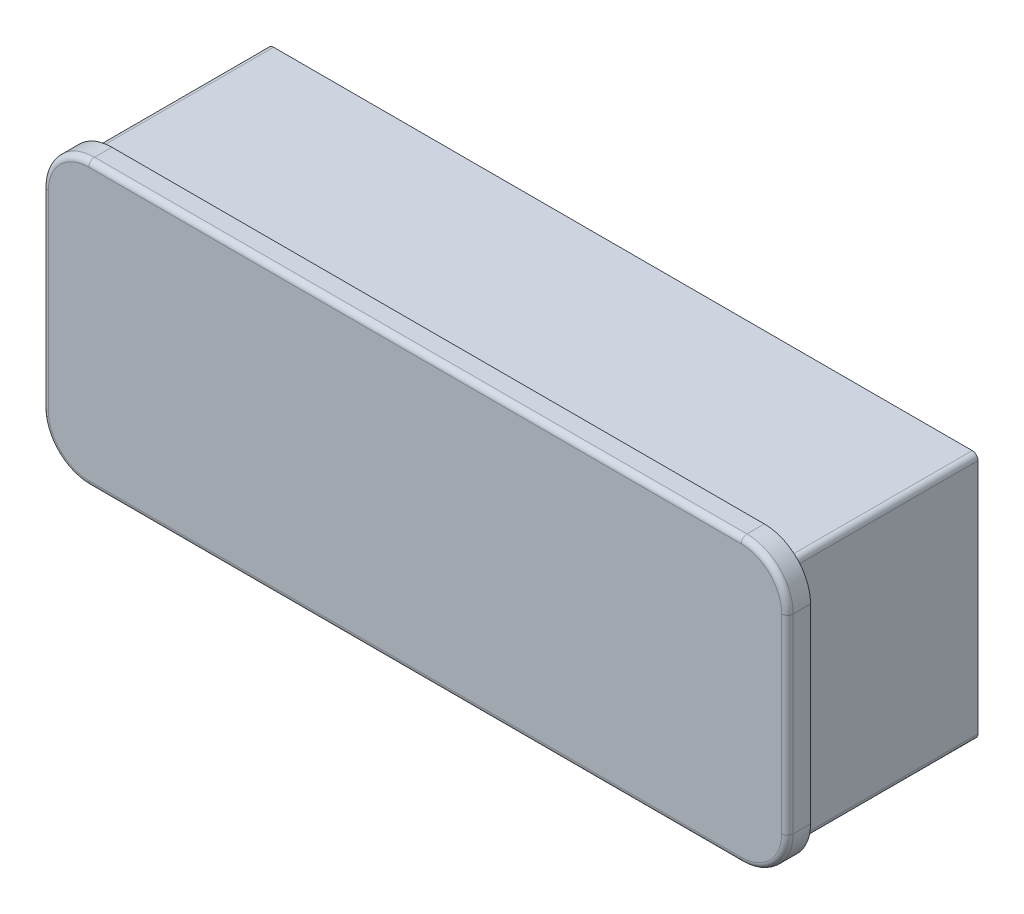
SolidWorks part; units mm, degrees
material "ABS"
ref_plane "Front Plane" through (0, 0, 0) normal (0, 0, 1) x (1, 0, 0)
ref_plane "Top Plane" through (0, 0, 0) normal (0, 1, 0) x (1, 0, 0)
ref_plane "Right Plane" through (0, 0, 0) normal (1, 0, 0) x (0, 0, -1)
sketch "Sketch1" plane through (0, 0, 0) normal (0, 0, 1) x (1, 0, 0)
  line L4 (-15.5, 32.5) -> (15.5, 32.5) construction
  line L5 (15.5, 32.5) -> (15.5, 43.5) construction
  line L6 (15.5, 43.5) -> (-15.5, 43.5) construction
  line L7 (-15.5, 43.5) -> (-15.5, 32.5) construction
  line L8 (-15.373, 32.627) -> (15.373, 32.627)
  line L9 (15.373, 32.627) -> (15.373, 43.373)
  line L10 (15.373, 43.373) -> (-15.373, 43.373)
  line L11 (-15.373, 43.373) -> (-15.373, 32.627)
  line L16 (14.623, 42.623) -> (-14.623, 42.623)
  line L17 (-14.623, 42.623) -> (-14.623, 33.377)
  line L18 (-14.623, 33.377) -> (14.623, 33.377)
  line L19 (14.623, 33.377) -> (14.623, 42.623)
  dimension "D1" = 0.127
  dimension "D2" = 0.75
extrude "Boss-Extrude1" add sketch "Sketch1" along normal blind 8
sketch "Sketch2" plane through (0, 0, 8) normal (0, 0, 1) x (1, 0, 0)
  line L22 (16.123, 31.877) -> (16.123, 44.123)
  line L23 (-16.123, 31.877) -> (16.123, 31.877)
  line L24 (-16.123, 44.123) -> (-16.123, 31.877)
  line L25 (16.123, 44.123) -> (-16.123, 44.123)
  line L26 (16.123, 31.877) -> (16.123, 44.123)
  line L27 (-16.123, 31.877) -> (16.123, 31.877)
  line L28 (-16.123, 44.123) -> (-16.123, 31.877)
  line L29 (16.123, 44.123) -> (-16.123, 44.123)
  dimension "D1" = 0.75
extrude "Boss-Extrude2" add sketch "Sketch2" along normal blind 1
fillet "Fillet2" radius 0.25 4 edges at (15.373, 32.627, 4) (-15.373, 32.627, 4) (-15.373, 43.373, 4) (15.373, 43.373, 4)
fillet "Fillet3" radius 2 4 edges at (16.123, 44.123, 8.5) (16.123, 31.877, 8.5) (-16.123, 31.877, 8.5) (-16.123, 44.123, 8.5)
fillet "Fillet4" radius 1 4 edges at (-14.623, 42.623, 4) (14.623, 42.623, 4) (14.623, 33.377, 4) (-14.623, 33.377, 4)
fillet "Fillet5" radius 0.25 8 edges at (15.5372, 32.4628, 9) (0, 31.877, 9) (-15.5372, 32.4628, 9) (-16.123, 38, 9) (-15.5372, 43.5372, 9) (0, 44.123, 9) (15.5372, 43.5372, 9) (16.123, 38, 9)
